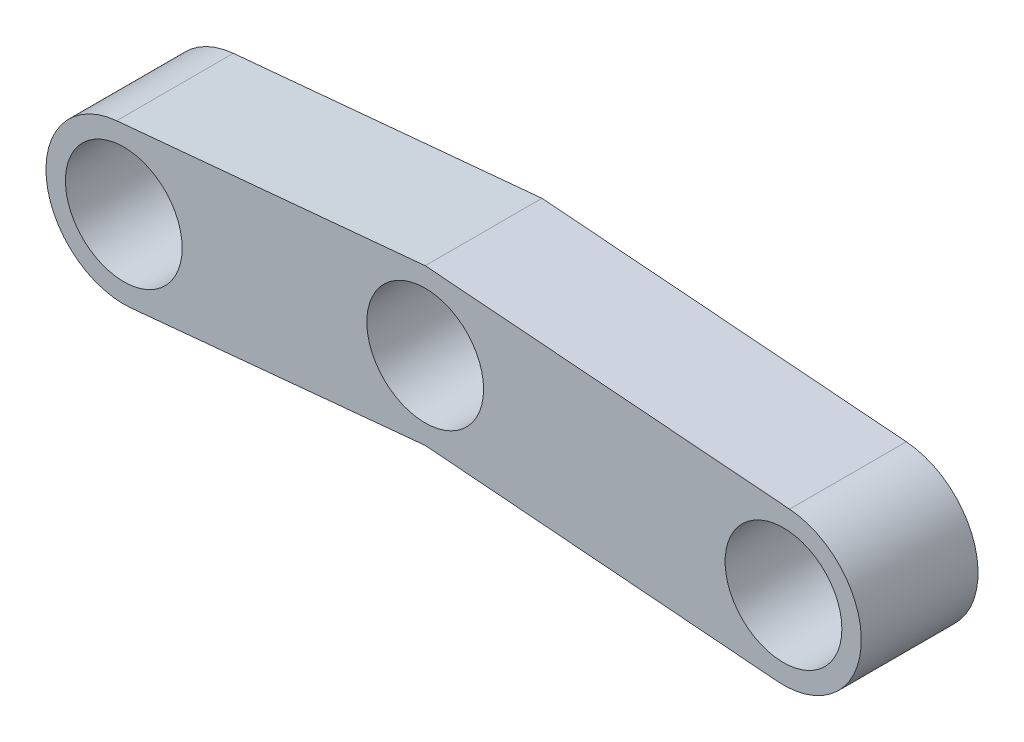
SolidWorks part; units mm, degrees
ref_plane "Front Plane" through (0, 0, 0) normal (0, 0, 1) x (1, 0, 0)
ref_plane "Top Plane" through (0, 0, 0) normal (0, 1, 0) x (1, 0, 0)
ref_plane "Right Plane" through (0, 0, 0) normal (1, 0, 0) x (0, 0, -1)
sketch "Sketch1" plane through (0, 0, 0) normal (0, 0, 1) x (1, 0, 0)
  line L0 (-1.8548, 19.9138) -> (77.4467, 27.3)
  line L1 (77.4467, 27.3) -> (171.0853, 19.9385)
  line L2 (1.9, -19.9095) -> (77.4467, -12.7)
  line L3 (77.4467, -12.7) -> (167.9233, -19.9363)
  line L4 (0, 0) -> (169.5178, 0) construction
  line L5 (77.4467, 7.3) -> (77.4467, 27.3) construction
  line L6 (77.4467, 7.3) -> (77.4467, -12.7) construction
  circle A0 centre (77.4467, 7.3) radius 15
  circle A1 centre (169.5178, 0) radius 15
  circle A2 centre (0, 0) radius 15
  arc A3 (-1.8548, 19.9138) -> (1.9, -19.9095) centre (0, 0) ccw
  arc A4 (171.0853, 19.9385) -> (167.9233, -19.9363) centre (169.5178, 0) cw
  point P5 (35, 4.7229)
  point P11 (0, 0)
  point P15 (0, 9.8295)
  point P18 (3.3216, 8.9609)
  point P19 (0, 0)
  dimension "D2" = 30
  dimension "D3" = 92.36
  dimension "D4" = 5
  dimension "D5" = 20
  dimension "D7" = 5
  dimension "D8" = 30
  dimension "D6" = 30
  dimension "D9" = 77.79
  dimension "D10" = 5
  dimension "D11" = 7.3
  dimension "D12" = 169.5178
extrude "Boss-Extrude1" add sketch "Sketch1" along normal blind 30
